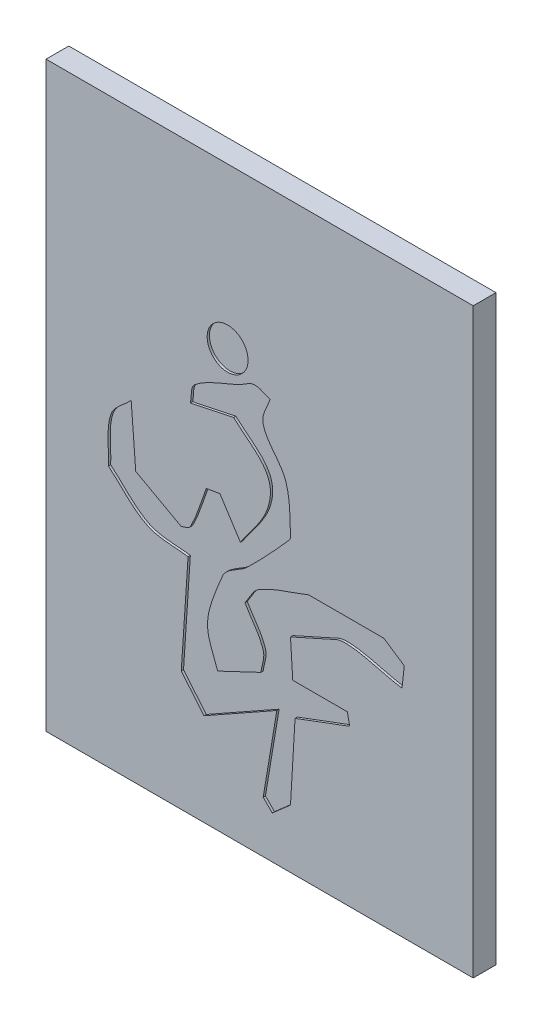
SolidWorks part; units mm, degrees
ref_plane "Plan de face" through (0, 0, 0) normal (0, 0, 1) x (1, 0, 0)
ref_plane "Plan de dessus" through (0, 0, 0) normal (0, 1, 0) x (1, 0, 0)
ref_plane "Plan de droite" through (0, 0, 0) normal (1, 0, 0) x (0, 0, -1)
sketch "Esquisse2" plane through (0, 0, 0) normal (0, 0, 1) x (1, 0, 0)
  line L1 (-93.8465, -127.9009) -> (93.8465, -127.9009)
  line L2 (-93.8465, -127.9009) -> (-93.8465, 127.9009)
  line L3 (-93.8465, 127.9009) -> (93.8465, 127.9009)
  line L4 (93.8465, -127.9009) -> (93.8465, 127.9009)
  line L5 (-93.8465, -127.9009) -> (93.8465, 127.9009) construction
  line L6 (-93.8465, 127.9009) -> (93.8465, -127.9009) construction
  point P0 (0, 0)
extrude "Boss.-Extru.1" add sketch "Esquisse2" against normal blind 10
sketch "Esquisse1" plane through (0, 0, 0) normal (0, 0, 1) x (1, 0, 0)
  line L59 (-18.4381, -67.2493) -> (0.5619, -58.2493)
  line L60 (21.5619, -18.2493) -> (54.5619, -18.2493)
  line L61 (54.5619, -18.2493) -> (63.5619, -24.2493)
  line L62 (63.5619, -24.2493) -> (62.5619, -33.2493)
  line L63 (13.5619, -38.2493) -> (14.5619, -54.2493)
  line L64 (14.5619, -54.2493) -> (38.5619, -54.2493)
  line L65 (38.5619, -54.2493) -> (39.5619, -59.2493)
  line L66 (39.5619, -59.2493) -> (15.5619, -68.2493)
  line L67 (15.5619, -68.2493) -> (13.5619, -102.2493)
  line L68 (13.5619, -102.2493) -> (5.5619, -109.2493)
  line L69 (5.5619, -109.2493) -> (1.5619, -105.2493)
  line L70 (1.5619, -105.2493) -> (7.5619, -69.2493)
  line L71 (7.5619, -69.2493) -> (-24.4381, -87.2493)
  line L72 (-24.4381, -87.2493) -> (-34.4381, -75.2493)
  line L73 (-34.4381, -75.2493) -> (-31.4381, -30.2493)
  line L74 (-56.4381, 16.7507) -> (-54.4381, -9.2493)
  line L75 (-54.4381, -9.2493) -> (-34.4381, -20.2493)
  line L76 (-23.4381, -0.2493) -> (-17.4381, 0.7507)
  line L77 (-17.4381, 0.7507) -> (-8.4381, -13.2493)
  line L78 (-11.4381, 32.7507) -> (-30.4381, 28.7507)
  circle A1 centre (-14.0685, 57.651) radius 8.9809
  spline S19 degree 3 poles (-30.4381, 28.7507) (-29.7714, 31.4174) (-30.5655, 35.0101) (-28.4381, 36.7507) (-22.6694, 41.4706) (-15.1048, 43.4174) (-8.4381, 46.7507) (-6.4381, 47.7507) (-4.6676, 49.5792) (-2.4381, 49.7507) (-0.0185, 49.9368) (2.2286, 48.4174) (4.5619, 47.7507) knots 0 0 0 0 1 1 1 2 2 2 3 3 3 4 4 4 4
  spline S20 degree 3 poles (4.5619, 47.7507) (3.5619, 44.0841) (0.6401, 40.4378) (1.5619, 36.7507) (3.1564, 30.3727) (9.5337, 26.0044) (11.5619, 19.7507) (13.6289, 13.3776) (13.2577, 6.4437) (13.5619, -0.2493) (13.5958, -0.9939) (13.062, -1.6966) (12.5619, -2.2493) (6.7087, -8.7186) (0.8381, -15.1895) (-5.4381, -21.2493) (-8.8463, -24.54) (-14.5997, -25.883) (-16.4381, -30.2493) (-25.6474, -52.1214) (-23.8007, -52.9489) (-18.4381, -67.2493) knots 0 0 0 0 1 1 1 2 2 2 3 3 3 4 4 4 5 5 5 6 6 6 7 7 7 7
  spline S21 degree 3 poles (0.5619, -58.2493) (0.8952, -55.2493) (2.4408, -52.137) (1.5619, -49.2493) (-0.003, -44.1073) (-3.7714, -39.9159) (-6.4381, -35.2493) knots 0 0 0 0 1 1 1 2 2 2 2
  spline S22 degree 3 poles (-6.4381, -35.2493) (-4.4381, -32.5826) (-3.2874, -28.9792) (-0.4381, -27.2493) (6.3346, -23.1373) (14.2286, -21.2493) (21.5619, -18.2493) knots 0 0 0 0 1 1 1 2 2 2 2
  spline S23 degree 3 poles (62.5619, -33.2493) (54.3481, -32.2225) (39.6194, -26.4959) (33.5619, -29.2493) (26.9066, -32.2744) (20.2286, -35.2493) (13.5619, -38.2493) knots 0 0 0 0 1 1 1 2 2 2 2
  spline S24 degree 3 poles (-31.4381, -30.2493) (-37.4381, -29.2493) (-43.9666, -29.9069) (-49.4381, -27.2493) (-56.0413, -24.042) (-60.7714, -17.9159) (-66.4381, -13.2493) knots 0 0 0 0 1 1 1 2 2 2 2
  spline S25 degree 3 poles (-66.4381, -13.2493) (-66.1048, -6.5826) (-67.5489, 0.4183) (-65.4381, 6.7507) (-64.02, 11.0051) (-59.4381, 13.4174) (-56.4381, 16.7507) knots 0 0 0 0 1 1 1 2 2 2 2
  spline S26 degree 3 poles (-34.4381, -20.2493) (-33.1048, -19.5826) (-31.1565, -19.5555) (-30.4381, -18.2493) (-27.3356, -12.6084) (-25.7714, -6.2493) (-23.4381, -0.2493) knots 0 0 0 0 1 1 1 2 2 2 2
  spline S27 degree 3 poles (-8.4381, -13.2493) (-4.4381, -6.9159) (1.1931, -1.3556) (3.5619, 5.7507) (8.3988, 20.2615) (-2.5724, 24.5183) (-11.4381, 32.7507) knots 0 0 0 0 1 1 1 2 2 2 2
extrude "Enlèv. mat.-Extru.1" cut sketch "Esquisse1" against normal blind 1
